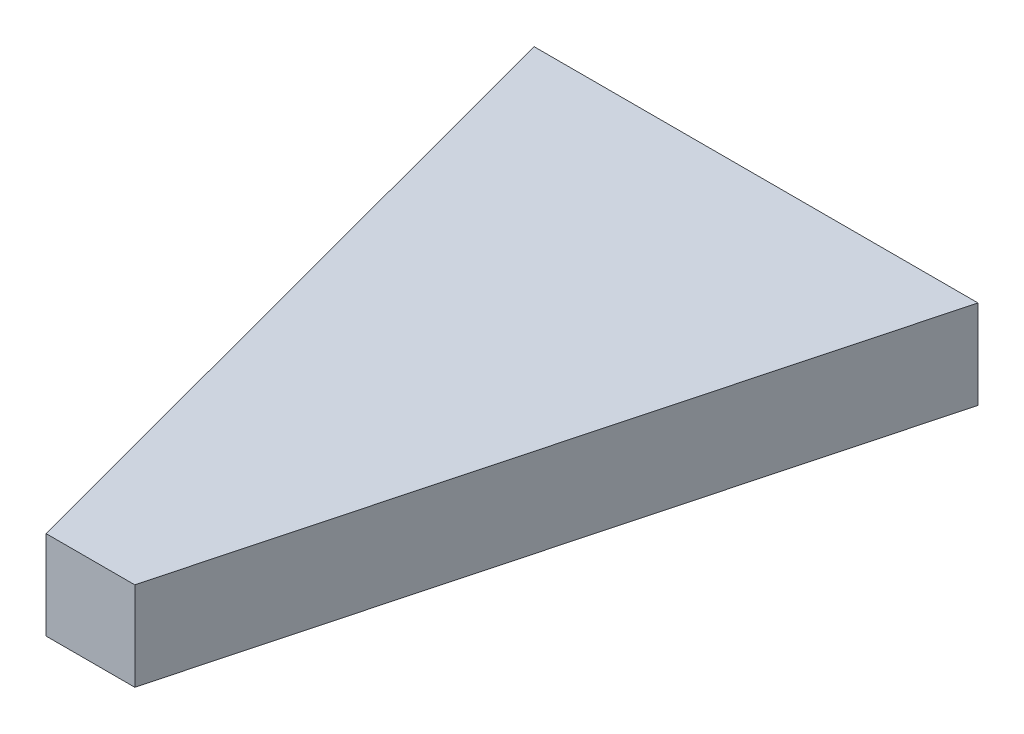
SolidWorks part; units mm, degrees
ref_plane "Front Plane" through (0, 0, 0) normal (0, 0, 1) x (1, 0, 0)
ref_plane "Top Plane" through (0, 0, 0) normal (0, 1, 0) x (1, 0, 0)
ref_plane "Right Plane" through (0, 0, 0) normal (1, 0, 0) x (0, 0, -1)
sketch "Virtual cargo" plane through (0, 0, 0) normal (0, 1, 0) x (1, 0, 0)
  line L1 (-55.2524, 24.0778) -> (-15.2524, 24.0778)
  line L2 (-55.2524, 24.0778) -> (-39.2524, -35.9222)
  line L3 (-39.2524, -35.9222) -> (-31.2524, -35.9222)
  line L4 (-15.2524, 24.0778) -> (-31.2524, -35.9222)
  point P6 (-35.2524, -35.9222)
  point P7 (-35.2524, 24.0778)
  dimension "D1" = 40
  dimension "D2" = 8
  dimension "D3" = 60
extrude "Virtual cargo extrude" add sketch "Virtual cargo" along normal blind 8
sketch "Sketch1" plane through (0, 0, 0) normal (0, 1, 0) x (1, 0, 0)
  line L0 (-76.152, 97.6216) -> (-46.152, 127.6216)
  line L1 (-78.0768, 80.1896) -> (-48.0768, 80.1896)
  line L2 (-78.0768, 80.1896) -> (-78.0768, 77.1896)
  line L3 (-78.0768, 77.1896) -> (-48.0768, 77.1896)
  line L4 (-48.0768, 80.1896) -> (-48.0768, 77.1896)
  line L5 (-76.152, 97.6216) -> (-76.152, 94.6216)
  line L6 (-76.152, 94.6216) -> (-46.152, 94.6216)
  line L7 (-46.152, 127.6216) -> (-46.152, 94.6216)
  line L8 (-76.152, 101.1378) -> (-76.152, 97.6216) construction
  line L9 (-77.5796, 72.0485) -> (-47.5796, 72.0485)
  line L10 (-77.5796, 72.0485) -> (-77.5796, 57.0485)
  line L11 (-77.5796, 57.0485) -> (-47.5796, 57.0485)
  line L12 (-47.5796, 72.0485) -> (-47.5796, 57.0485)
  line L13 (-77.6763, 118.4335) -> (-77.6763, 49.0833) construction
  point P8 (0, 0)
  dimension "D1" = 30
  dimension "D2" = 3
  dimension "D3" = 135
  dimension "D4" = 30
  dimension "D5" = 3
  dimension "D6" = 30
  dimension "D7" = 15
